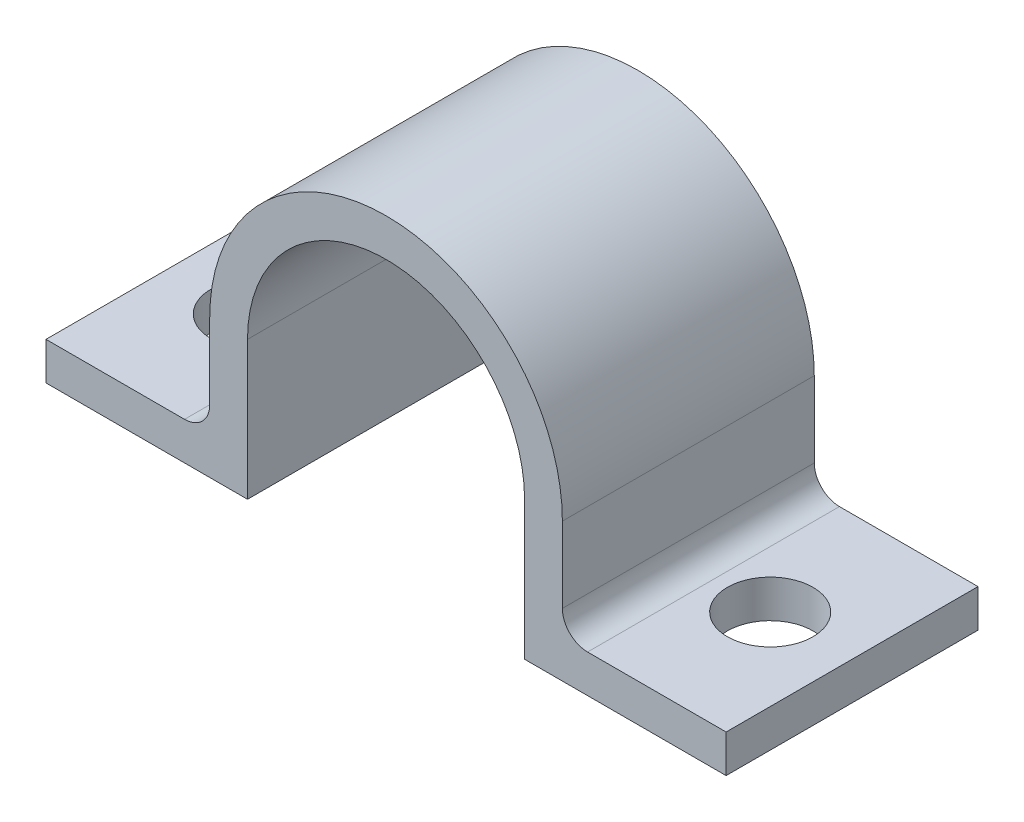
SolidWorks part; units mm, degrees
ref_plane "Front" through (0, 0, 0) normal (0, 0, 1) x (1, 0, 0)
ref_plane "Top" through (0, 0, 0) normal (0, 1, 0) x (1, 0, 0)
ref_plane "Right" through (0, 0, 0) normal (1, 0, 0) x (0, 0, -1)
sketch "Sketch1" plane through (0, 0, 0) normal (0, 0, 1) x (1, 0, 0)
  line L0 (-13.5, 0) -> (-13.5, 1.5)
  line L4 (5.5, 0) -> (5.5, 5.5)
  line L5 (0, 11) -> (0, 0) construction
  line L11 (-7, 1.5) -> (-13.5, 1.5)
  line L12 (-5.5, 0) -> (-13.5, 0)
  line L13 (-7, 1.5) -> (-7, 5.5)
  line L19 (7, 1.5) -> (7, 5.5)
  line L20 (5.5, 0) -> (13.5, 0)
  line L22 (7, 1.5) -> (13.5, 1.5)
  line L23 (13.5, 0) -> (13.5, 1.5)
  line L24 (-5.5, 0) -> (-5.5, 5.5)
  arc A0 (-5.5, 5.5) -> (5.5, 5.5) centre (0, 5.5) cw
  arc A1 (-7, 5.5) -> (7, 5.5) centre (0, 5.5) cw
  point P0 (0, 0)
  dimension "D1" = 5.5
  dimension "D3" = 1.5
  dimension "D5" = 1.5
  dimension "D6" = 8
  dimension "D2" = 11
extrude "Boss-Extrude1" add sketch "Sketch1" along normal blind 10
sketch "Sketch2" plane through (0, 1.5, 0) normal (0, 1, 0) x (1, 0, 0)
  line L0 (7, -10) -> (7, 0) construction
  line L2 (13.5, 0) -> (7, 0) construction
  circle A0 centre (10.25, -5) radius 1.7
  point P5 (7, -5)
  point P7 (10.25, 0)
  dimension "D1" = 3.4
extrude "Cut-Extrude1" cut sketch "Sketch2" against normal through all
fillet "Fillet1" radius 1 2 edges at (7, 1.5, 5) (-7, 1.5, 5)
mirror "Mirror1" about plane through (0, 0, 0) normal (1, 0, 0) of "Cut-Extrude1"
equation "\"Jack Diameter\"= 11"
equation "\"Jack Width\"= 19.63"
equation "\"Wall Thickness\"= 1.5"
equation "\"Mount Length\" = 10"
equation "\"D1@Boss-Extrude1\"=\"Mount Length\""
equation "\"D3@Sketch1\"=\"Wall Thickness\""
equation "\"D1@Sketch1\"=\"Jack Diameter\"/2"
equation "\"D2@Sketch1\"=\"Jack Diameter\""
